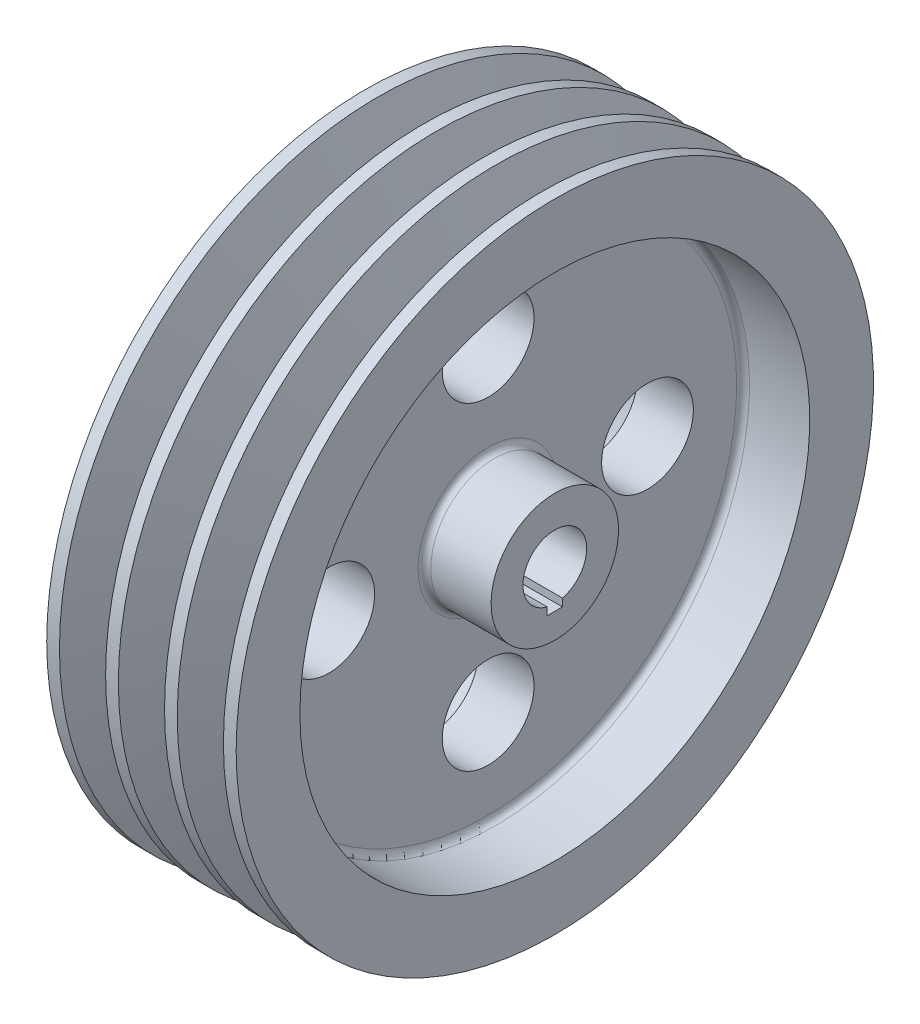
SolidWorks part; units mm, degrees
ref_plane "Front Plane" through (0, 0, 0) normal (0, 0, 1) x (1, 0, 0)
ref_plane "Top Plane" through (0, 0, 0) normal (0, 1, 0) x (1, 0, 0)
ref_plane "Right Plane" through (0, 0, 0) normal (1, 0, 0) x (0, 0, -1)
sketch "Sketch1" plane through (0, 0, 0) normal (0, 1, 0) x (1, 0, 0)
  line L0 (0, 125) -> (0, 100)
  line L1 (0, 125) -> (5, 125)
  line L2 (5, 125) -> (11.5515, 107)
  line L3 (11.5515, 107) -> (16.5515, 107)
  line L4 (-67.944, 0) -> (117.6123, 0) construction
  line L5 (16.5515, 107) -> (23.1029, 125)
  line L6 (23.1029, 125) -> (28.1029, 125)
  line L7 (28.1029, 125) -> (34.6544, 107)
  line L8 (34.6544, 107) -> (39.6544, 107)
  line L10 (46.2059, 125) -> (39.6544, 107)
  line L11 (51.2059, 125) -> (46.2059, 125)
  line L12 (57.7573, 107) -> (51.2059, 125)
  line L13 (62.7573, 107) -> (57.7573, 107)
  line L14 (69.3088, 125) -> (62.7573, 107)
  line L15 (74.3088, 125) -> (69.3088, 125)
  line L16 (74.3088, 125) -> (74.3088, 100)
  line L17 (0, 100) -> (23.6544, 100)
  line L18 (2.5, 25) -> (23.6544, 25)
  line L19 (37.1544, 163.3327) -> (37.1544, -29.8744) construction
  line L20 (26.1544, 97.5) -> (26.1544, 27.5)
  line L21 (48.1544, 97.5) -> (48.1544, 27.5)
  line L22 (50.6544, 25) -> (71.8088, 25)
  line L23 (50.6544, 100) -> (74.3088, 100)
  line L24 (0, 12.5) -> (74.3088, 12.5)
  line L25 (0, 22.5) -> (0, 12.5)
  line L26 (74.3088, 22.5) -> (74.3088, 12.5)
  line L27 (2.5, 25) -> (0, 25)
  line L28 (0, 25) -> (0, 22.5)
  line L29 (71.8088, 25) -> (74.3088, 25)
  line L30 (74.3088, 25) -> (74.3088, 22.5)
  arc A0 (26.1544, 97.5) -> (23.6544, 100) centre (23.6544, 97.5) ccw
  arc A1 (48.1544, 97.5) -> (50.6544, 100) centre (50.6544, 97.5) cw
  arc A2 (23.6544, 25) -> (26.1544, 27.5) centre (23.6544, 27.5) ccw
  arc A3 (50.6544, 25) -> (48.1544, 27.5) centre (50.6544, 27.5) cw
  dimension "D14" = 5
  dimension "D15" = 5
  dimension "D2" = 5
  dimension "D3" = 5
  dimension "D4" = 18
  dimension "D5" = 25
  dimension "D6" = 40
  dimension "D7" = 5
  dimension "D8" = 18
  dimension "D9" = 25
  dimension "D10" = 0
  dimension "D11" = 2.5
  dimension "D12" = 22
  dimension "D13" = 11
  dimension "D16" = 12.5
revolve "Revolve1" add sketch "Sketch1" angle 360 about L4
sketch "Sketch5" plane through (26.1544, 0, 0) normal (-1, 0, 0) x (0, 0, 1)
  line L0 (0, 134.5982) -> (0, -140.1909) construction
  line L1 (-168.0256, 0) -> (173.3532, 0) construction
  circle A0 centre (0, 0) radius 62.5
  circle A1 centre (0, 62.5) radius 18
  circle A2 centre (62.5, 0) radius 18
  circle A3 centre (0, -62.5) radius 18
  circle A4 centre (-62.5, 0) radius 18
  circle A5 centre (0, 0) radius 25
  circle A6 centre (0, 0) radius 12.5
  point P18 (0, 0)
  dimension "D1" = 125
  dimension "D2" = 36
  dimension "D4" = 50
  dimension "D5" = 25
  dimension "D3" = 4
extrude "Cut-Extrude1" cut sketch "Sketch5" against normal through all contours A0 A1 | A0 A1 | A0 A4 | A0 A4 | A0 A3 | A0 A3 | A0 A2 | A0 A2 | A6
sketch "Sketch6" plane through (0, 0, 0) normal (-1, 0, 0) x (0, 0, 1)
  line L0 (-3, -12.1347) -> (-3, -15.1347)
  line L1 (-3, -15.1347) -> (3, -15.1347)
  line L2 (3, -15.1347) -> (3, -12.1347)
  circle A0 centre (0, 0) radius 12.5 construction
  arc A1 (-3, -12.1347) -> (3, -12.1347) centre (0, 0) ccw
  dimension "D1" = 6
  dimension "D2" = 3
  dimension "D3" = 3
extrude "Cut-Extrude2" cut sketch "Sketch6" against normal through all
